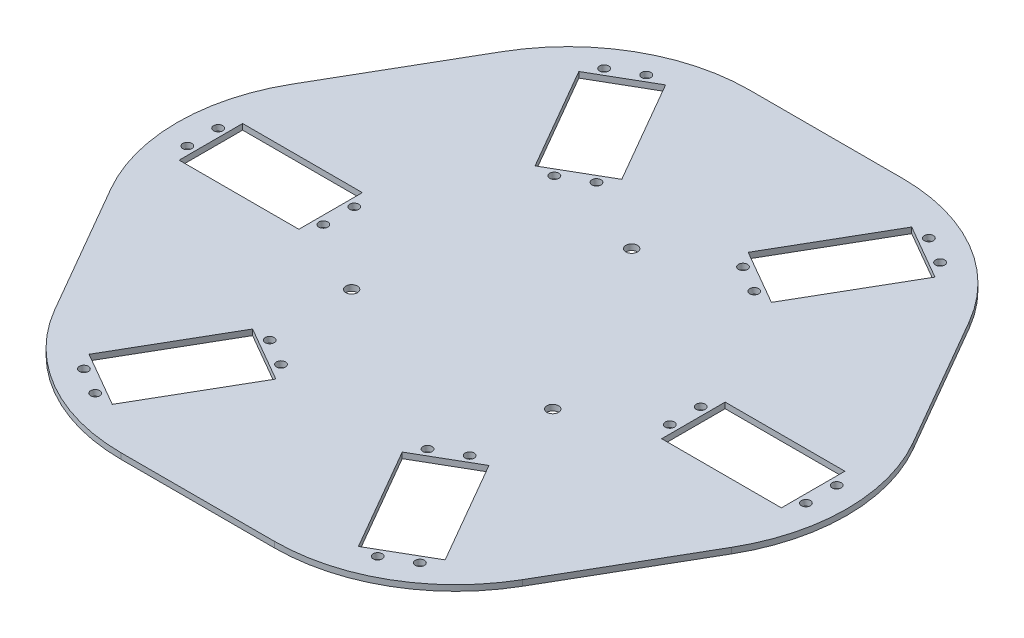
SolidWorks part; units mm, degrees
material "Acrylic (Medium-high impact)"
ref_plane "Front Plane" through (0, 0, 0) normal (0, 0, 1) x (1, 0, 0)
ref_plane "Top Plane" through (0, 0, 0) normal (0, 1, 0) x (1, 0, 0)
ref_plane "Right Plane" through (0, 0, 0) normal (1, 0, 0) x (0, 0, -1)
sketch "Sketch1" plane through (0, 0, 0) normal (0, 1, 0) x (1, 0, 0)
  line L0 (0, 0) -> (200, 0)
  line L1 (171.1325, 50) -> (128.8675, 123.2051)
  line L2 (42.265, 173.2051) -> (-42.265, 173.2051)
  line L3 (-128.8675, 123.2051) -> (-171.1325, 50)
  line L4 (-171.1325, -50) -> (-128.8675, -123.2051)
  line L5 (-42.265, -173.2051) -> (42.265, -173.2051)
  line L6 (128.8675, -123.2051) -> (171.1325, -50)
  line L7 (100, 17.5) -> (166, 17.5)
  line L8 (100, 17.5) -> (100, -17.5)
  line L9 (166, 17.5) -> (166, -17.5)
  line L10 (100, -17.5) -> (166, -17.5)
  line L11 (0, -55) -> (0, 55) construction
  line L12 (-55, 0) -> (55, 0) construction
  line L13 (65.1554, -77.8525) -> (98.1554, -135.0102)
  line L14 (65.1554, -77.8525) -> (34.8446, -95.3525)
  line L15 (34.8446, -95.3525) -> (67.8446, -152.5102)
  line L16 (98.1554, -135.0102) -> (67.8446, -152.5102)
  line L17 (-34.8446, -95.3525) -> (-67.8446, -152.5102)
  line L18 (-34.8446, -95.3525) -> (-65.1554, -77.8525)
  line L19 (-65.1554, -77.8525) -> (-98.1554, -135.0102)
  line L20 (-67.8446, -152.5102) -> (-98.1554, -135.0102)
  line L21 (-100, -17.5) -> (-166, -17.5)
  line L22 (-100, -17.5) -> (-100, 17.5)
  line L23 (-100, 17.5) -> (-166, 17.5)
  line L24 (-166, -17.5) -> (-166, 17.5)
  line L25 (-65.1554, 77.8525) -> (-98.1554, 135.0102)
  line L26 (-65.1554, 77.8525) -> (-34.8446, 95.3525)
  line L27 (-34.8446, 95.3525) -> (-67.8446, 152.5102)
  line L28 (-98.1554, 135.0102) -> (-67.8446, 152.5102)
  line L29 (34.8446, 95.3525) -> (67.8446, 152.5102)
  line L30 (34.8446, 95.3525) -> (65.1554, 77.8525)
  line L31 (65.1554, 77.8525) -> (98.1554, 135.0102)
  line L32 (67.8446, 152.5102) -> (98.1554, 135.0102)
  circle A0 centre (0, 0) radius 200 construction
  circle A1 centre (170.5, 8.5) radius 2.5
  circle A2 centre (170.5, -8.5) radius 2.5
  circle A3 centre (95.5, 8.5) radius 2.5
  circle A4 centre (95.5, -8.5) radius 2.5
  circle A5 centre (40.3888, -86.9554) radius 2.5
  circle A6 centre (55.1112, -78.4554) radius 2.5
  circle A7 centre (92.6112, -143.4073) radius 2.5
  circle A8 centre (77.8888, -151.9073) radius 2.5
  circle A9 centre (-55.1112, -78.4554) radius 2.5
  circle A10 centre (-40.3888, -86.9554) radius 2.5
  circle A11 centre (-77.8888, -151.9073) radius 2.5
  circle A12 centre (-92.6112, -143.4073) radius 2.5
  circle A13 centre (-95.5, 8.5) radius 2.5
  circle A14 centre (-95.5, -8.5) radius 2.5
  circle A15 centre (-170.5, -8.5) radius 2.5
  circle A16 centre (-170.5, 8.5) radius 2.5
  circle A17 centre (-40.3888, 86.9554) radius 2.5
  circle A18 centre (-55.1112, 78.4554) radius 2.5
  circle A19 centre (-92.6112, 143.4073) radius 2.5
  circle A20 centre (-77.8888, 151.9073) radius 2.5
  circle A21 centre (55.1112, 78.4554) radius 2.5
  circle A22 centre (40.3888, 86.9554) radius 2.5
  circle A23 centre (77.8888, 151.9073) radius 2.5
  circle A24 centre (92.6112, 143.4073) radius 2.5
  arc A25 (-42.265, 173.2051) -> (-128.8675, 123.2051) centre (-42.265, 73.2051) ccw
  arc A26 (-171.1325, 50) -> (-171.1325, -50) centre (-84.5299, 0) ccw
  arc A27 (-128.8675, -123.2051) -> (-42.265, -173.2051) centre (-42.265, -73.2051) ccw
  arc A28 (42.265, -173.2051) -> (128.8675, -123.2051) centre (42.265, -73.2051) ccw
  arc A29 (171.1325, -50) -> (171.1325, 50) centre (84.5299, 0) ccw
  arc A30 (128.8675, 123.2051) -> (42.265, 173.2051) centre (42.265, 73.2051) ccw
  point P88 (0, 0)
  point P94 (100, -173.2051)
  dimension "D1" = 400
  dimension "D7" = 5
  dimension "D8" = 5
  dimension "D9" = 5
  dimension "D10" = 5
  dimension "D20" = 100
  dimension "D2" = 200
  dimension "D3" = 66
  dimension "D4" = 35
  dimension "D5" = 100
  dimension "D6" = 17.5
  dimension "D11" = 17
  dimension "D12" = 17
  dimension "D13" = 75
  dimension "D14" = 0
  dimension "D15" = 4.5
  dimension "D16" = 0
  dimension "D17" = 9
  dimension "D18" = 9
  dimension "D19" = 6
extrude "Boss-Extrude1" add sketch "Sketch1" along normal blind 3.175
sketch "Sketch2" plane through (0, 3.175, 0) normal (0, 1, 0) x (1, 0, 0)
  line L0 (0, -1.1339) -> (85.0289, -1.1339)
  line L1 (0, -1.7463) -> (0, 1.7463) construction
  line L2 (55.7942, -33.3467) -> (0, -1.1339)
  circle A0 centre (55.7942, -33.3467) radius 3.2
  circle A1 centre (-56.7762, -31.6459) radius 3.2
  circle A2 centre (0.982, 64.9926) radius 3.2
  point P14 (0, 0)
  dimension "D3" = 6.4
  dimension "D1" = 65
  dimension "D2" = 30
  dimension "D4" = 3
extrude "Cut-Extrude1" cut sketch "Sketch2" against normal up to surface (3.175 mm away) contours A2 | A0 | A1 up to face at (0, 0, 0)
